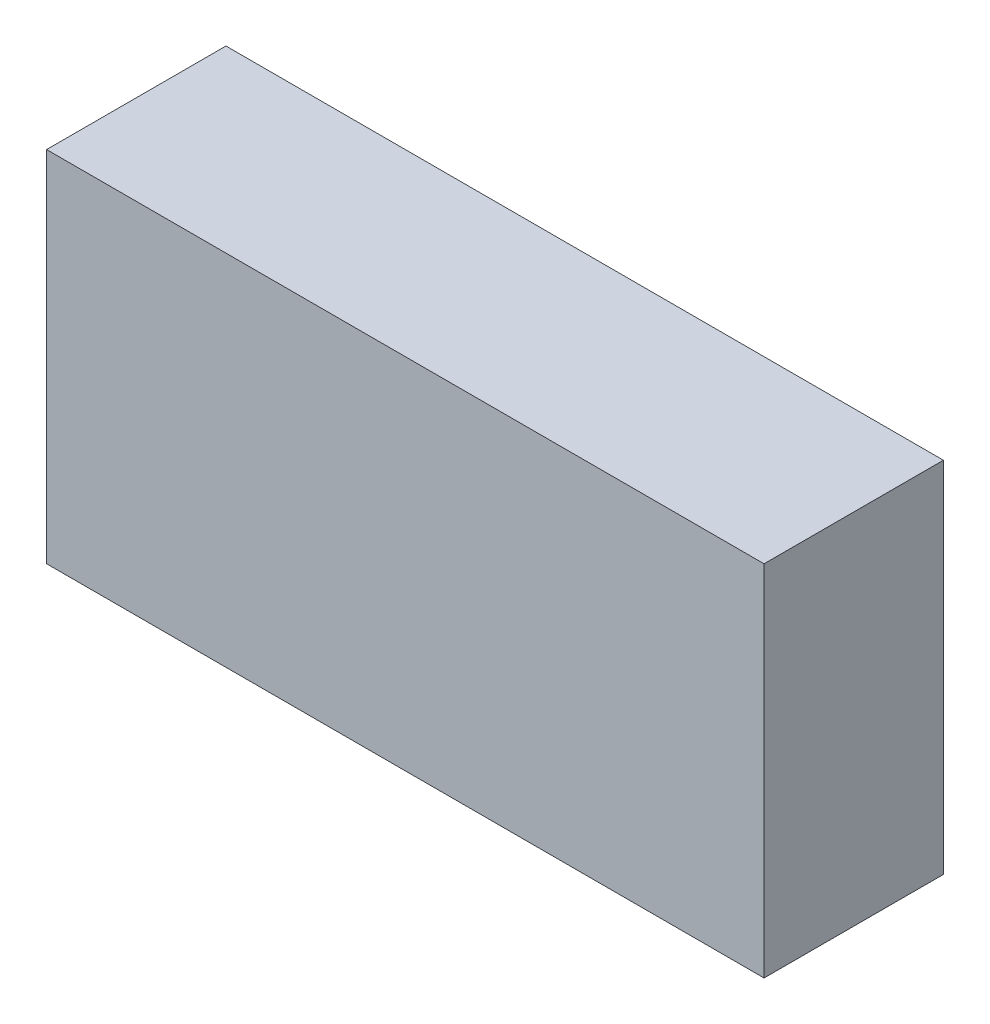
SolidWorks part; units mm, degrees
ref_plane "Front Plane" through (0, 0, 0) normal (0, 0, 1) x (1, 0, 0)
ref_plane "Top Plane" through (0, 0, 0) normal (0, 1, 0) x (1, 0, 0)
ref_plane "Right Plane" through (0, 0, 0) normal (1, 0, 0) x (0, 0, -1)
sketch "Sketch1" plane through (0, 0, 0) normal (0, 0, 1) x (1, 0, 0)
  line L1 (0, 0) -> (40, 0)
  line L2 (0, 0) -> (0, 20)
  line L3 (0, 20) -> (40, 20)
  line L4 (40, 0) -> (40, 20)
extrude "Boss-Extrude1" add sketch "Sketch1" along normal blind 10
